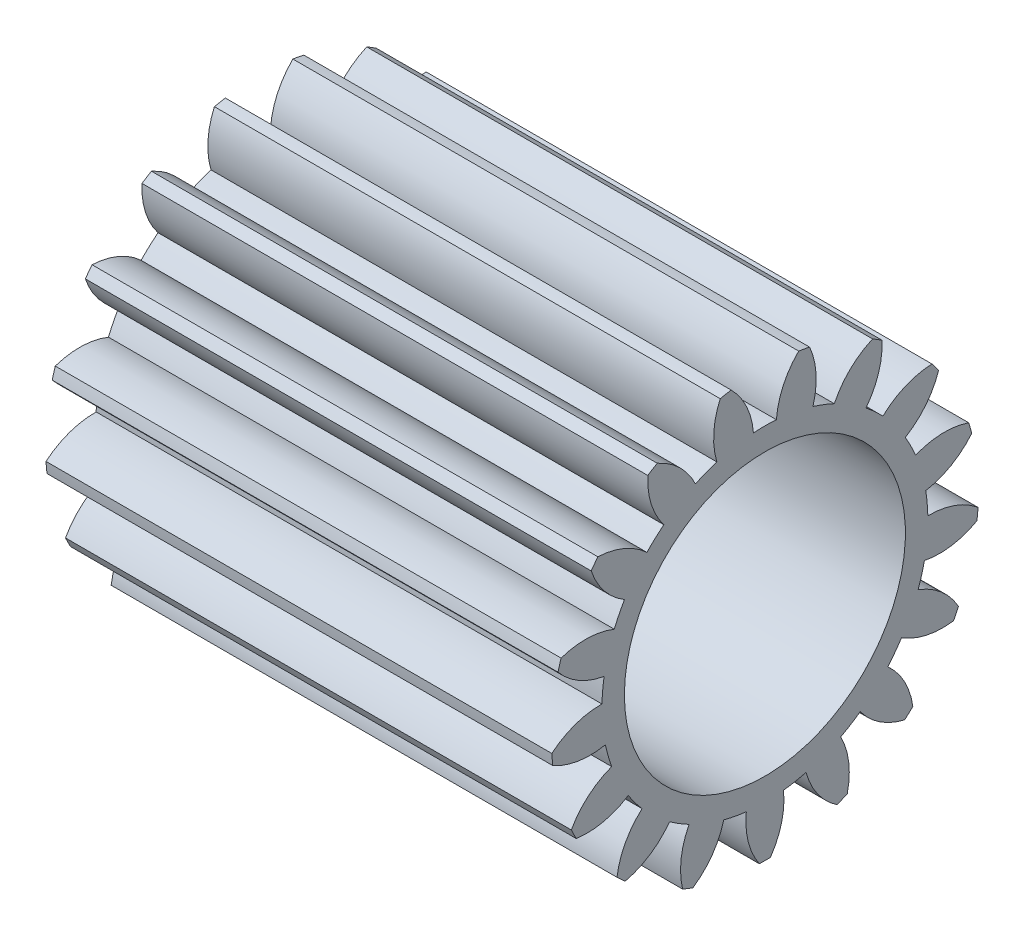
SolidWorks part; units mm, degrees
ref_plane "Plane1" through (0, 0, 0) normal (0, 0, 1) x (1, 0, 0)
ref_plane "Plane2" through (0, 0, 0) normal (0, 1, 0) x (1, 0, 0)
ref_plane "Plane3" through (0, 0, 0) normal (1, 0, 0) x (0, 0, -1)
other "Configuration Table"
sketch "HoldingSke" plane through (0, 0, 0) normal (0, 1, 0) x (1, 0, 0)
  line L0 (0, 0) -> (0.4782, -0.1462)
  line L1 (-15, 0) -> (100, 0) construction
  line L2 (0, 0) -> (-2.1039, 2.3779)
  line L3 (0, 0) -> (-11.863, 4.5341)
  line L4 (0, 0) -> (8.2586, 2.5249)
  line L5 (0, 0) -> (-46.8476, -17.4728)
  line L6 (0, 0) -> (-37.3033, -25.1687)
  line L7 (-2.1039, 2.3779) -> (8.6586, 51.2059)
  line L8 (-76.2, 54.61) -> (-72.9, 54.61)
  line L9 (-71.009, 38.7566) -> (-53.1078, 45.2721)
  line L10 (-76.2, 71.12) -> (104.1128, 71.12)
  line L11 (0, 0) -> (-45, 0)
  line L12 (-76.2, 101.6) -> (-76.133, 101.6)
  line L13 (24.9733, 27.94) -> (52.9518, 28.4284)
  line L14 (24.9733, 27.94) -> (24.9743, 27.94)
  line L15 (24.9733, 27.94) -> (100.4006, 29.5858)
  line L16 (-63.627, -2) -> (-12.827, -2)
  circle A0 centre (0, 0) radius 12.5
  circle A1 centre (0, 0) radius 14.499
  circle A2 centre (0, 0) radius 37.5
  circle A3 centre (0, 0) radius 12.5
  dimension "MHD" = 28.998
  dimension "Hub_dia" = 75
  dimension "Bore" = 25
  dimension "MBD" = 25
  dimension "Num_teeth" = 17
  dimension "Pitch" = 0.5
  dimension "Overall_len" = 50
  dimension "Show_teeth" = 17
  dimension "Thickness" = 45
  dimension "OAL" = 50.0001
  dimension "T_dim" = 3.3
  dimension "Ap" = 20
  dimension "H" = 19.05
  dimension "Pitch_radius" = 180.3128
  dimension "Width" = 45
  dimension "Backlash" = 0.067
  dimension "Addendum_fac" = 1
  dimension "Dedendum_fac" = 1.25
  dimension "Clearance_fac" = 0.25
  dimension "Dedendum_add" = 0.001
  dimension "Module" = 2
sketch "BasProSke" plane through (0, 0, 0) normal (0, 1, 0) x (1, 0, 0)
  line L0 (-10, 0) -> (60, 0) construction
  line L1 (0, 0) -> (0, 19)
  line L2 (0, 0) -> (45, 0)
  line L3 (45, 0) -> (45, 19)
  line L4 (45, 19) -> (0, 19)
  dimension "Thickness" = 45
  dimension "Diameter" = 38
revolve "Base-Revolve" add sketch "BasProSke" angle 360 about L0
sketch "TooCutSke" plane through (0, 0, 0) normal (1, 0, 0) x (0, 0, -1)
  line L1 (0, 0) -> (0, 107) construction
  line L2 (0, 0) -> (-1.6857, 16.9162) construction
  line L3 (0, 0) -> (-6.2247, 33.2991) construction
  line L4 (-1.6857, 16.9162) -> (-3.1123, 16.6495) construction
  arc A0 (1.0204, 14.4631) -> (-1.0204, 14.4631) centre (0, 0) ccw
  arc A1 (3.0261, 18.7832) -> (-3.0261, 18.7832) centre (0, 0) ccw
  circle A2 centre (0, 0) radius 17 construction
  circle A3 centre (0, 0) radius 15.9748 construction
  arc A4 (-1.0204, 14.4631) -> (-3.0261, 18.7832) centre (-7.8003, 13.9409) ccw
  arc A5 (3.0261, 18.7832) -> (1.0204, 14.4631) centre (7.8003, 13.9409) ccw
  dimension "Root_dia" = 28.998
  dimension "Overcut_dia" = 38.0508
  dimension "Pitch_dia" = 34
  dimension "Base_dia" = 31.9495
  dimension "Flank_rad" = 6.8
  dimension "Half_ang" = 10.588
  dimension "Half_CT" = 1.4513
extrude "ToothCut" cut sketch "TooCutSke" along normal through all
fillet "Breaks" [suppressed] radius 0.04
fillet "RootFillets" [suppressed] radius 0.501
pattern_circular "TeethCuts" count 17 every 21.176 about axis through (-10, 0, 0) along (1, 0, 0) of "ToothCut", "RootFillets", "Breaks"
sketch "HubNeaOneSke" plane through (0, 0, 0) normal (-1, 0, 0) x (0, 0, 1)
  circle A0 centre (0, 0) radius 14.499
  dimension "Diameter" = 28.998
extrude "HubNearOne" [suppressed] add sketch "HubNeaOneSke" along normal blind 5.0001
sketch "HubNeaBotSke" plane through (0, 0, 0) normal (-1, 0, 0) x (0, 0, 1)
  circle A0 centre (0, 0) radius 14.499
  dimension "Diameter" = 28.998
extrude "HubNearBoth" [suppressed] add sketch "HubNeaBotSke" along normal blind 2.5
ref_plane "FarPln" through (45, 0, 0) normal (1, 0, 0) x (0, 0, -1)
sketch "HubFarSke" plane through (45, 0, 0) normal (1, 0, 0) x (0, 0, -1)
  circle A0 centre (0, 0) radius 14.499
  dimension "Diameter" = 28.998
extrude "HubFar" [suppressed] add sketch "HubFarSke" along normal blind 2.5
sketch "BorSke" plane through (0, 0, 0) normal (1, 0, 0) x (0, 0, -1)
  circle A0 centre (0, 0) radius 12.5
  dimension "Diameter" = 25
extrude "Bore" cut sketch "BorSke" along normal mid plane 100.0001
sketch "KeySke" plane through (0, 0, 0) normal (1, 0, 0) x (0, 0, -1)
  line L0 (-4, 0) -> (-4, 15.8)
  line L1 (-4, 15.8) -> (4, 15.8)
  line L2 (4, 15.8) -> (4, 0)
  line L3 (0, 0) -> (0, 34) construction
  line L4 (-4, 0) -> (4, 0)
  dimension "Offset" = 15.8
  dimension "Width" = 8
extrude "Keyway" [suppressed] cut sketch "KeySke" along normal mid plane 100.0001
pattern_circular "Keyway2" [suppressed] count 2 every 90 about axis through (-10, 0, 0) along (1, 0, 0)
equation "' \"Module@HoldingSke\" = 6.35"
equation "' \"Num_teeth@HoldingSke\" = 12"
equation "' \"Ap@HoldingSke\" =  20"
equation "' \"Ap@HoldingSke\" = 20"
equation "' \"Width@HoldingSke\" = 0.5 * 25.4"
equation "' \"Hub_dia@HoldingSke\"= 1 * 25.4"
equation "' \"Hub_dia@HoldingSke\" = 1 * 25.4"
equation "' \"Overall_len@HoldingSke\" = 1.0 * 25.4"
equation "' \"Bore@HoldingSke\" = 0.75 * 25.4"
equation "' \"T_dim@HoldingSke\" = 0.1 * 25.4"
equation "' \"Width@KeySke\" = 0.25 * 25.4"
equation "' \"Show_teeth@HoldingSke\" = 13"
equation "' \"Backlash@HoldingSke\" = 0.009 * 25.4"
equation "' \"Addendum_fac@HoldingSke\" = 1.0"
equation "' \"Dedendum_fac@HoldingSke\" = 1.25"
equation "' \"Dedendum_add@HoldingSke\" = 0.00005 * 25.4"
equation "' \"Clearance_fac@HoldingSke\" = 0.25"
equation "\"Pitch@HoldingSke\" = 1 / \"Module@HoldingSke\""
equation "\"Overcut_dia@TooCutSke\" = (\"Num_teeth@HoldingSke\" + 2 * \"Addendum_fac@HoldingSke\") / \"Pitch@HoldingSke\" + 0.002 * 25.4"
equation "\"Pitch_dia@TooCutSke\" = \"Num_teeth@HoldingSke\" / \"Pitch@HoldingSke\""
equation "\"Base_dia@TooCutSke\" = \"Num_teeth@HoldingSke\" / \"Pitch@HoldingSke\" * cos((\"Ap@HoldingSke\"  * 3.14159265 / 180))"
equation "\"Root_dia@TooCutSke\" = (\"Num_teeth@HoldingSke\" + 2) / \"Pitch@HoldingSke\" - 2 * (\"Addendum_fac@HoldingSke\" + \"Dedendum_fac@HoldingSke\") / \"Pitch@HoldingSke\" - \"Dedendum_add@HoldingSke\" * 2"
equation "\"Half_ang@TooCutSke\" = 180 / \"Num_teeth@HoldingSke\""
equation "\"Half_CT@TooCutSke\" = \"Num_teeth@HoldingSke\" / \"Pitch@HoldingSke\" * sin((3.14159265 / 2 / \"Num_teeth@HoldingSke\")) / 2 - 7 * \"Backlash@HoldingSke\" / 4"
equation "\"Flank_rad@TooCutSke\" = \"Num_teeth@HoldingSke\" / \"Pitch@HoldingSke\" / 5"
equation "\"Radius@RootFillets\" = \"Clearance_fac@HoldingSke\" / \"Pitch@HoldingSke\" + \"Dedendum_add@HoldingSke\""
equation "\"Break_rad@Breaks\" = 0.02 / \"Pitch@HoldingSke\""
equation "\"Thickness@HoldingSke\" = \"Width@HoldingSke\""
equation "\"OAL@HoldingSke\" = \"Thickness@HoldingSke\""
equation "\"MHD@HoldingSke\" = (\"Num_teeth@HoldingSke\" + 2) / \"Pitch@HoldingSke\" - 2 * (\"Addendum_fac@HoldingSke\" + \"Dedendum_fac@HoldingSke\")  / \"Pitch@HoldingSke\" - \"Dedendum_add@HoldingSke\" * 2"
equation "\"MBD@HoldingSke\" = (\"Num_teeth@HoldingSke\" + 2) / \"Pitch@HoldingSke\" - 2 * (\"Addendum_fac@HoldingSke\" + \"Dedendum_fac@HoldingSke\")  / \"Pitch@HoldingSke\" - \"Dedendum_add@HoldingSke\" * 2 - 0.002 * 25.4"
equation "\"MHD@HoldingSke\" = ((sgn( \"MHD@HoldingSke\" - \"Hub_dia@HoldingSke\" )-1)*( \"MHD@HoldingSke\" - \"Hub_dia@HoldingSke\" ))/-2+ \"Hub_dia@HoldingSke\""
equation "\"MBD@HoldingSke\" = ((sgn( \"MBD@HoldingSke\" - \"Bore@HoldingSke\" )-1)*( \"MBD@HoldingSke\" - \"Bore@HoldingSke\" ))/-2+ \"Bore@HoldingSke\""
equation "\"OAL@HoldingSke\" = ((sgn( \"OAL@HoldingSke\" - \"Overall_len@HoldingSke\" )+1)*( \"OAL@HoldingSke\" - \"Overall_len@HoldingSke\" ))/2 + \"Overall_len@HoldingSke\" + 0.000002 * 25.4"
equation "\"Num_teeth@TeethCuts\" = int( \"Show_teeth@HoldingSke\" ) + 1"
equation "\"Num_teeth@TeethCuts\" = ((sgn( \"Num_teeth@TeethCuts\" - \"Num_teeth@HoldingSke\" )-1)*( \"Num_teeth@TeethCuts\" - \"Num_teeth@HoldingSke\" ))/-2+ \"Num_teeth@HoldingSke\""
equation "\"Num_teeth@TeethCuts\" = ((sgn( \"Num_teeth@TeethCuts\" - 2.0)+1)*( \"Num_teeth@TeethCuts\" - 2.0))/2 +2.0"
equation "\"Angle@TeethCuts\" = 360.0 / \"Num_teeth@HoldingSke\""
equation "\"Diameter@BasProSke\" = (\"Num_teeth@HoldingSke\" + 2 * \"Addendum_fac@HoldingSke\") / \"Pitch@HoldingSke\""
equation "\"Thickness@BasProSke\"  = \"Thickness@HoldingSke\""
equation "' \"Fillet_rad@BasProSke\" =  \"Thickness@HoldingSke\" * 0.05"
equation "' \"Fillet_rad@BasProSke\" = \"Thickness@HoldingSke\" * 0.05"
equation "\"MHD@HoldingSke\" = ((sgn( \"MHD@HoldingSke\" - \"Root_dia@TooCutSke\" )-1)*( \"MHD@HoldingSke\" - \"Root_dia@TooCutSke\" ))/-2+ \"Root_dia@TooCutSke\""
equation "\"Diameter@HubNeaOneSke\" = \"MHD@HoldingSke\""
equation "\"Length@HubNearOne\" = \"OAL@HoldingSke\" - \"Thickness@BasProSke\""
equation "\"Diameter@HubNeaBotSke\" = \"MHD@HoldingSke\""
equation "\"Length@HubNearBoth\" = ( \"OAL@HoldingSke\" - \"Thickness@BasProSke\" ) / 2.0"
equation "\"Thickness@FarPln\" = \"Thickness@BasProSke\""
equation "\"Diameter@HubFarSke\" = \"MHD@HoldingSke\""
equation "\"Length@HubFar\" = ( \"OAL@HoldingSke\" - \"Thickness@BasProSke\" ) / 2.0"
equation "\"Diameter@BorSke\" = \"MBD@HoldingSke\""
equation "\"D1@Bore\" = \"OAL@HoldingSke\" * 2.0"
equation "\"D1@Keyway\" = \"OAL@HoldingSke\" * 2.0"
equation "\"Offset@KeySke\" = \"T_dim@HoldingSke\" + \"MBD@HoldingSke\" / 2.0"
